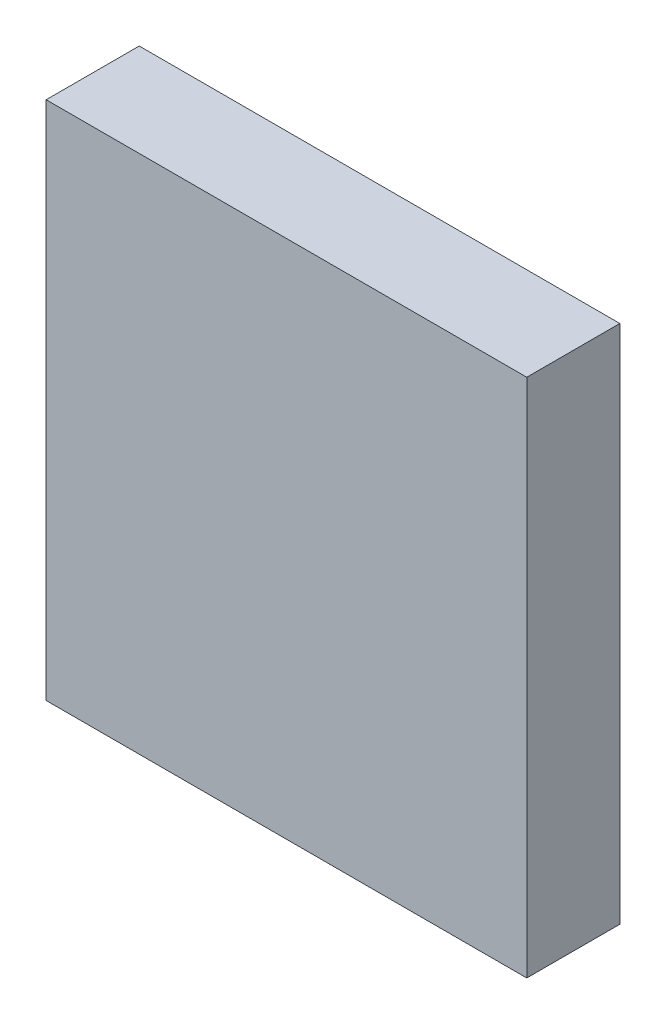
SolidWorks part; units mm, degrees
ref_plane "Front Plane" through (0, 0, 0) normal (0, 0, 1) x (1, 0, 0)
ref_plane "Top Plane" through (0, 0, 0) normal (0, 1, 0) x (1, 0, 0)
ref_plane "Right Plane" through (0, 0, 0) normal (1, 0, 0) x (0, 0, -1)
sketch "Sketch1" plane through (0, 0, 0) normal (0, 0, 1) x (1, 0, 0)
  line L0 (-2.8901, 2.5901) -> (2.2735, 2.5901)
  line L1 (2.2735, 2.5901) -> (2.2735, -3)
  line L2 (2.2735, -3) -> (-2.8901, -3)
  line L3 (-2.8901, -3) -> (-2.8901, 2.5901)
extrude "Component_Outline" add sketch "Sketch1" along normal blind 1 separate body
sketch3d "3DSketch1"
  line L0 (0, 0, 0) -> (1, 0, 0)
  line L1 (0, 0, 0) -> (0, 1, 0)
  line L2 (0, 0, 0) -> (0, 0, 1)
  point P0 (0, 0, 0)
